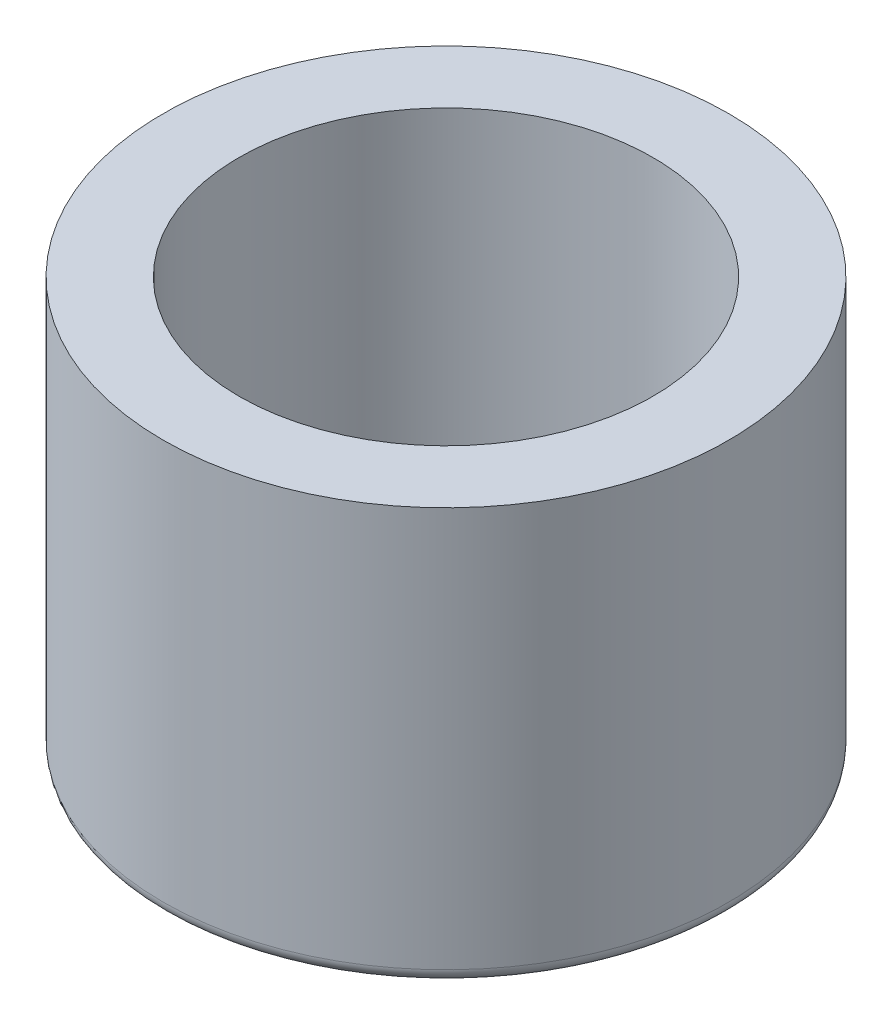
SolidWorks part; units mm, degrees
ref_plane "Front Plane" through (0, 0, 0) normal (0, 0, 1) x (1, 0, 0)
ref_plane "Top Plane" through (0, 0, 0) normal (0, 1, 0) x (1, 0, 0)
ref_plane "Right Plane" through (0, 0, 0) normal (1, 0, 0) x (0, 0, -1)
sketch "Sketch1" plane through (0, 0, 0) normal (0, 1, 0) x (1, 0, 0)
  circle A0 centre (0, 0) radius 10.25
  dimension "D1" = 20.5
extrude "Boss-Extrude1" add sketch "Sketch1" along normal blind 15
sketch "Sketch2" plane through (0, 15, 0) normal (0, 1, 0) x (1, 0, 0)
  circle A0 centre (0, 0) radius 7.5
  dimension "D1" = 15
extrude "Cut-Extrude1" cut sketch "Sketch2" against normal up to surface (15 mm away) up to face at (0, 0, 10.25)
fillet "Fillet1" radius 0.5 1 edges at (0, 0, 10.25)
